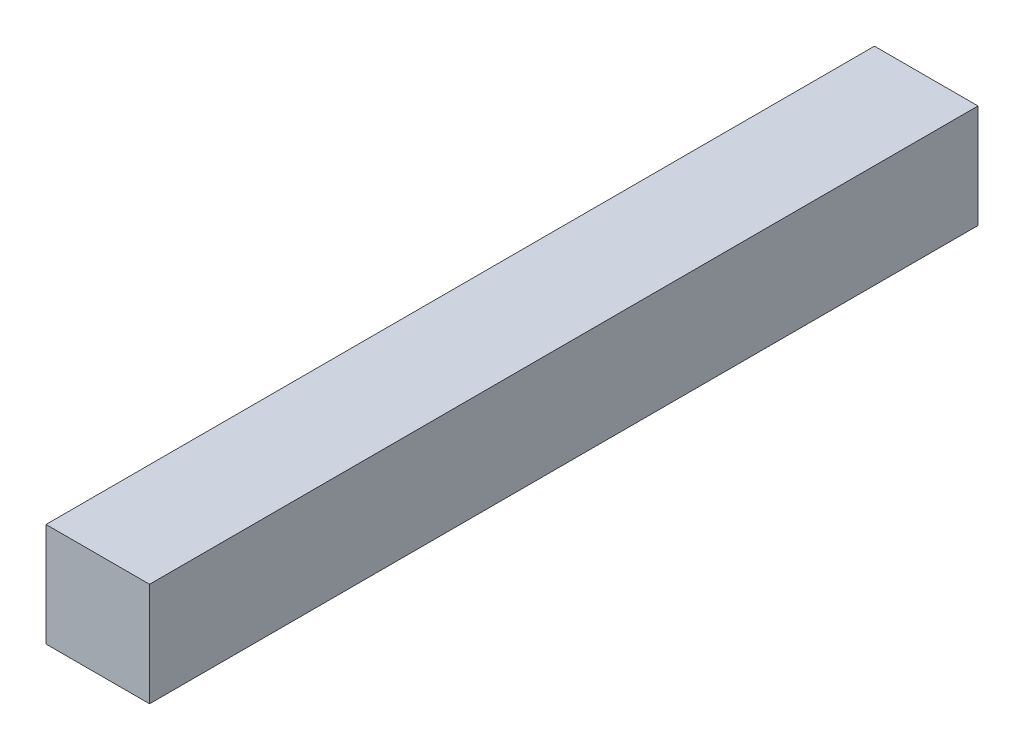
SolidWorks part; units mm, degrees
material "Carbon Fiber (Isotropic)"
ref_plane "Ön Düzlem" through (0, 0, 0) normal (0, 0, 1) x (1, 0, 0)
ref_plane "Üst Düzlem" through (0, 0, 0) normal (0, 1, 0) x (1, 0, 0)
ref_plane "Sağ Düzlem" through (0, 0, 0) normal (1, 0, 0) x (0, 0, -1)
sketch "Çizim1" plane through (0, 0, 0) normal (0, 0, 1) x (1, 0, 0)
  line L1 (-12.5, -12.5) -> (12.5, -12.5)
  line L2 (-12.5, -12.5) -> (-12.5, 12.5)
  line L3 (-12.5, 12.5) -> (12.5, 12.5)
  line L4 (12.5, -12.5) -> (12.5, 12.5)
  line L5 (-12.5, -12.5) -> (12.5, 12.5) construction
  line L6 (-12.5, 12.5) -> (12.5, -12.5) construction
  point P0 (0, 0)
  dimension "D1" = 25
  dimension "D2" = 25
extrude "Yükseklik-Ekstrüzyon1" add sketch "Çizim1" against normal blind 200
